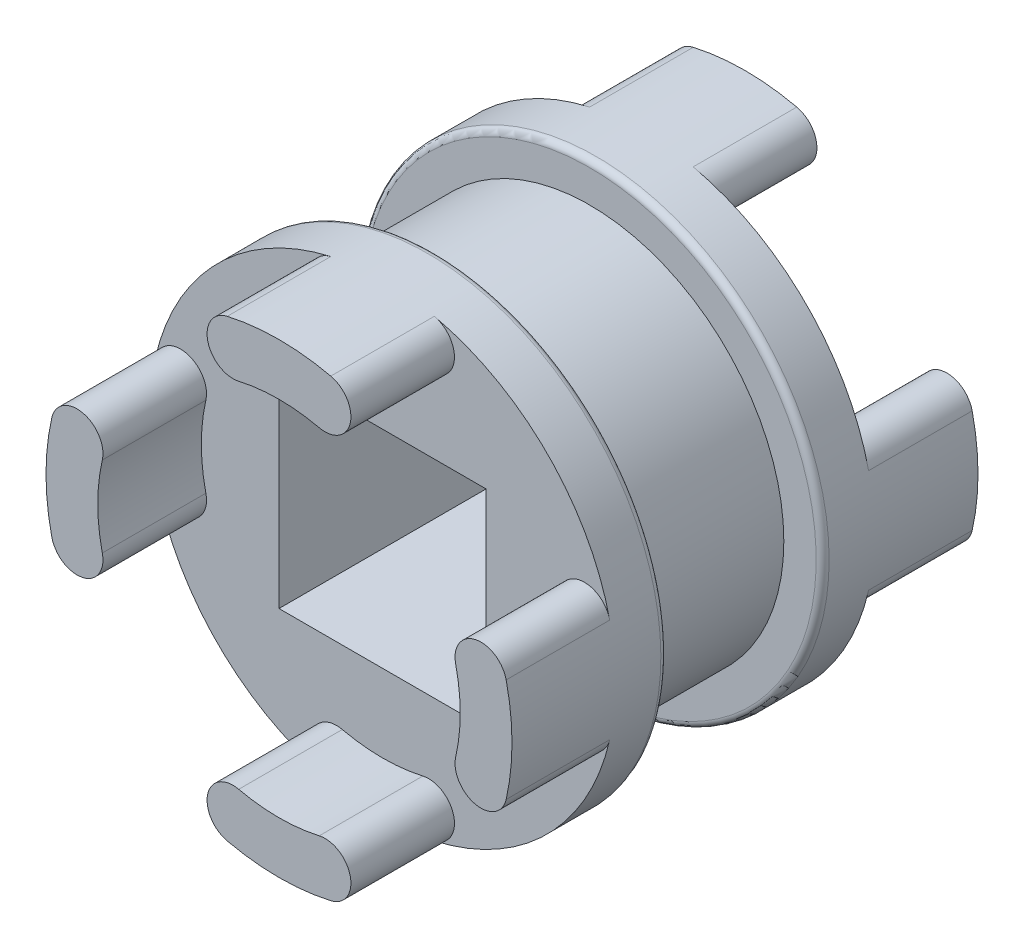
SolidWorks part; units mm, degrees
ref_plane "Front Plane" through (0, 0, 0) normal (0, 0, 1) x (1, 0, 0)
ref_plane "Top Plane" through (0, 0, 0) normal (0, 1, 0) x (1, 0, 0)
ref_plane "Right Plane" through (0, 0, 0) normal (1, 0, 0) x (0, 0, -1)
sketch "Sketch2" plane through (0, 0, 0) normal (1, 0, 0) x (0, 0, -1)
  line L0 (-5, 0) -> (-5, 9)
  line L1 (-5, 9) -> (-3, 9)
  line L2 (-3, 9) -> (-3, 7.5)
  line L3 (-3, 7.5) -> (3, 7.5)
  line L4 (0, -20.9183) -> (0, 20.9183) construction
  line L5 (-5, 0) -> (5, 0)
  line L6 (3, 9) -> (3, 7.5)
  line L7 (5, 9) -> (3, 9)
  line L8 (5, 0) -> (5, 9)
  line L9 (0, 0) -> (15.424, 0)
  line L10 (55, 0) -> (-55, 0) construction
  point P10 (0, 0)
  point P13 (0, 0)
  point P14 (0, 7.5)
  dimension "D1" = 9
  dimension "D2" = 1.5
  dimension "D3" = 6
  dimension "D4" = 2
revolve "Revolve1" add sketch "Sketch2" angle 360 about L9
fillet "Fillet2" radius 0.25 2 edges at (9, 0, -3) (9, 0, 3)
sketch "Sketch3" plane through (0, 0, -5) normal (0, 0, -1) x (-1, 0, 0)
  line L0 (0, 0) -> (0, 18.3802) construction
  line L1 (0, 55) -> (0, -55) construction
  line L2 (2, 8.775) -> (1.5556, 6.825) construction
  arc A0 (0, 9) -> (2, 8.775) centre (0, 0) cw
  arc A1 (0, 7) -> (1.5556, 6.825) centre (0, 0) cw
  circle A2 centre (1.7778, 7.8) radius 1
  arc A3 (0, 7) -> (-1.5556, 6.825) centre (0, 0) ccw
  arc A4 (0, 9) -> (-2, 8.775) centre (0, 0) ccw
  circle A5 centre (-1.7778, 7.8) radius 1
  dimension "D1" = 9
  dimension "D2" = 2
  dimension "D3" = 2
extrude "Boss-Extrude1" add sketch "Sketch3" along normal blind 4 contours A4 A5 A3 A1 A2 A0 | A5 | A2
pattern_circular "CirPattern1" count 4 over 360 about axis through (0, 0, 0) along (0, 0, 1) of "Boss-Extrude1"
mirror "Mirror1" about plane through (0, 0, 0) normal (0, 0, 1) of "CirPattern1", "Boss-Extrude1"
sketch "Sketch4" plane through (0, 0, -5) normal (0, 0, -1) x (-1, 0, 0)
  line L1 (-4, -4) -> (4, -4)
  line L2 (-4, -4) -> (-4, 4)
  line L3 (-4, 4) -> (4, 4)
  line L4 (4, -4) -> (4, 4)
  line L5 (-4, -4) -> (4, 4) construction
  line L6 (-4, 4) -> (4, -4) construction
  point P0 (0, 0)
  dimension "D1" = 8
extrude "Cut-Extrude1" cut sketch "Sketch4" against normal up to next
